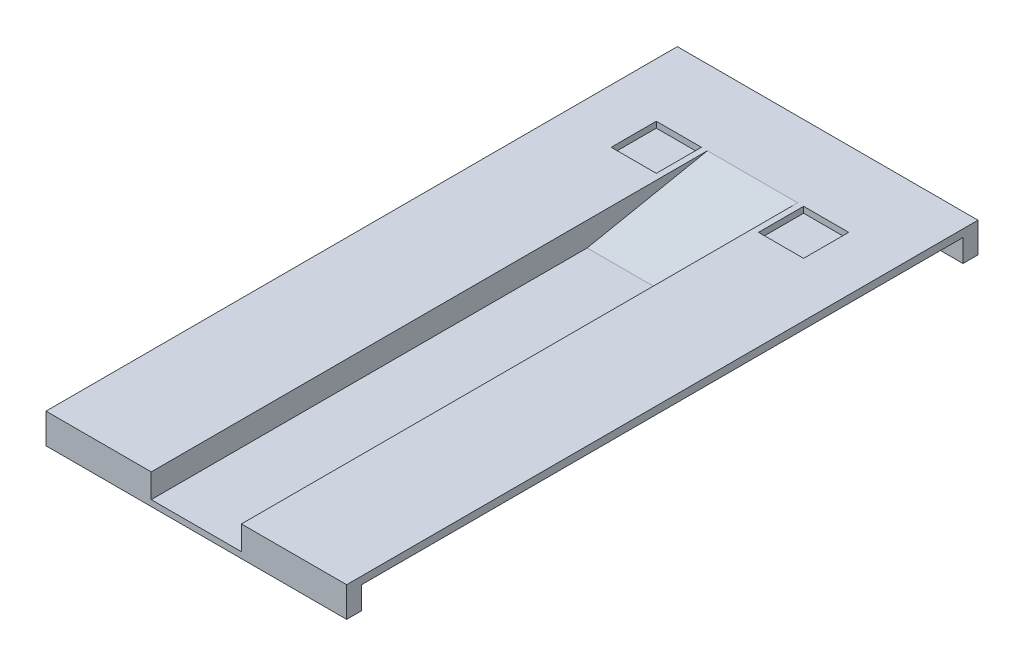
SolidWorks part; units mm, degrees
material "Thornel VCB-20 Carbon Cloth"
ref_plane "Front Plane" through (0, 0, 0) normal (0, 0, 1) x (1, 0, 0)
ref_plane "Top Plane" through (0, 0, 0) normal (0, 1, 0) x (1, 0, 0)
ref_plane "Right Plane" through (0, 0, 0) normal (1, 0, 0) x (0, 0, -1)
sketch "Sketch1" plane through (0, 0, 0) normal (0, 1, 0) x (1, 0, 0)
  line L0 (0, 0) -> (100, 0)
  line L1 (100, 0) -> (100, -210)
  line L2 (100, -210) -> (0, -210)
  line L3 (0, -210) -> (0, 0)
  dimension "D1" = 100
  dimension "D2" = 210
extrude "Boss-Extrude1" add sketch "Sketch1" along normal blind 10
sketch "Sketch2" plane through (0, 10, 0) normal (0, 1, 0) x (1, 0, 0)
  line L0 (35, -210) -> (35, -25)
  line L1 (0, -210) -> (100, -210) construction
  line L2 (0, 0) -> (0, -210) construction
  line L3 (65, -210) -> (65, -25)
  line L4 (65, -25) -> (35, -25)
  line L5 (100, -210) -> (100, 0) construction
  line L6 (35, -210) -> (65, -210)
  dimension "D1" = 35
  dimension "D2" = 35
extrude "Cut-Extrude2" cut sketch "Sketch2" against normal blind 8
sketch "Sketch3" plane through (65, 0, 0) normal (-1, 0, 0) x (0, 0, 1)
  line L0 (25, 2) -> (65, 2)
  line L1 (210, 2) -> (25, 2) construction
  line L2 (65, 2) -> (25, 10)
  line L3 (25, 10) -> (25, 2)
extrude "Boss-Extrude3" add sketch "Sketch3" along normal blind 30
sketch "Sketch4" plane through (100, 0, 0) normal (1, 0, 0) x (0, 0, -1)
  line L1 (-210, 0) -> (0, 0) construction
  line L2 (-205, 0) -> (-205, 7.5)
  line L3 (-205, 7.5) -> (-5, 7.5)
  line L4 (-5, 7.5) -> (-5, 0)
  line L5 (-5, 0) -> (-205, 0)
extrude "Cut-Extrude3" cut sketch "Sketch4" against normal blind 10
sketch "Sketch5" plane through (0, 0, 0) normal (-1, 0, 0) x (0, 0, 1)
  line L1 (0, 0) -> (210, 0) construction
  line L2 (5, 0) -> (5, 7.5)
  line L3 (5, 7.5) -> (205, 7.5)
  line L4 (205, 7.5) -> (205, 0)
  line L5 (205, 0) -> (5, 0)
extrude "Cut-Extrude4" cut sketch "Sketch5" against normal blind 10
sketch "Sketch6" plane through (0, 10, 0) normal (0, 1, 0) x (1, 0, 0)
  line L1 (33, -25) -> (33, -40)
  line L2 (33, -40) -> (18, -40)
  line L3 (18, -40) -> (18, -25)
  line L4 (18, -25) -> (33, -25)
  line L5 (67, -25) -> (67, -40)
  line L6 (67, -40) -> (82, -40)
  line L7 (82, -40) -> (82, -25)
  line L8 (82, -25) -> (67, -25)
extrude "Cut-Extrude5" cut sketch "Sketch6" against normal blind 2
